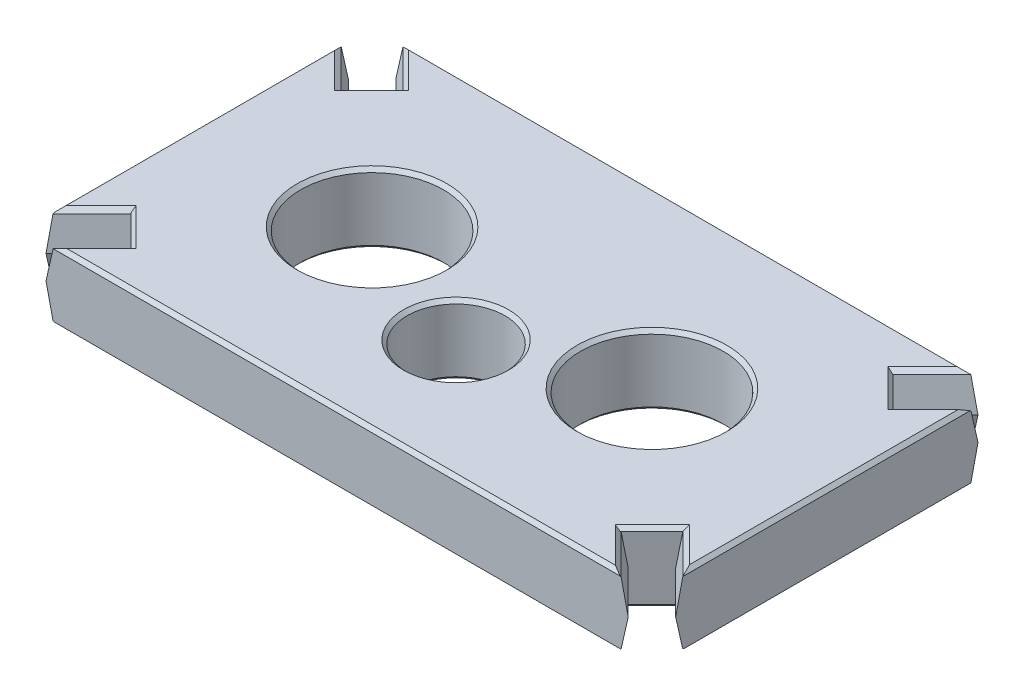
SolidWorks part; units mm, degrees
ref_plane "Front Plane" through (0, 0, 0) normal (0, 0, 1) x (1, 0, 0)
ref_plane "Top Plane" through (0, 0, 0) normal (0, 1, 0) x (1, 0, 0)
ref_plane "Right Plane" through (0, 0, 0) normal (1, 0, 0) x (0, 0, -1)
sketch "Sketch1" plane through (0, 0, 0) normal (0, 1, 0) x (1, 0, 0)
  line L0 (-10, 0) -> (10, 0) construction
  line L1 (-10, 12.5) -> (10, 12.5) construction
  line L2 (-10, -12.5) -> (10, -12.5) construction
  line L4 (22.5, -12.5) -> (-22.5, -12.5)
  line L5 (22.5, -12.5) -> (22.5, 12.5)
  line L6 (22.5, 12.5) -> (-22.5, 12.5)
  line L7 (-22.5, -12.5) -> (-22.5, 12.5)
  line L8 (22.5, -12.5) -> (-22.5, 12.5) construction
  line L9 (22.5, 12.5) -> (-22.5, -12.5) construction
  arc A0 (-10, 12.5) -> (-10, -12.5) centre (-10, 0) ccw construction
  arc A1 (10, -12.5) -> (10, 12.5) centre (10, 0) ccw construction
  circle A2 centre (-10, 0) radius 5.1
  circle A3 centre (10, 0) radius 5.1
  circle A4 centre (0, -4) radius 3.5
  point P2 (0, 0)
  point P12 (0, 0)
  point P19 (0, 0)
  dimension "D1" = 10.2
  dimension "D3" = 12.5
  dimension "D5" = 7
  dimension "D2" = 20
  dimension "D4" = 4
extrude "Boss-Extrude1" add sketch "Sketch1" along normal blind 5
ref_plane "Plane1" through (-17.5, 0, -17.5) normal (-0.7071, 0, -0.7071) x (0, -1, 0)
sketch "Sketch4" plane through (-17.5, 0, -17.5) normal (-0.7071, 0, -0.7071) x (0, -1, 0)
  line L0 (-5, 8.6711) -> (-5, 5.4711)
  line L1 (-5, 7.0711) -> (-5, 24.7487) construction
  line L2 (-5, -24.7487) -> (-5, 7.0711) construction
  line L3 (-5, 5.4711) -> (-2.5, 5.8711)
  line L4 (-2.5, 5.8711) -> (0, 5.4711)
  line L5 (0, -24.7487) -> (0, 7.0711) construction
  line L6 (0, 5.4711) -> (0, 8.6711)
  line L7 (0, 7.0711) -> (0, 24.7487) construction
  line L8 (0, 8.6711) -> (-2.5, 8.2711)
  line L9 (-2.5, 8.2711) -> (-5, 8.6711)
  line L10 (-2.5, 8.2711) -> (-2.5, 5.8711) construction
  line L11 (-5, 7.0711) -> (0, 7.0711) construction
  point P7 (-2.5, 7.0711)
  point P15 (0, 0)
  dimension "D1" = 3.2
  dimension "D2" = 2.4
extrude "Cut-Extrude3" cut sketch "Sketch4" against normal blind 5.5
mirror "Mirror1" about plane through (0, 0, 0) normal (0, 0, 1) of "Cut-Extrude3"
mirror "Mirror2" about plane through (0, 0, 0) normal (1, 0, 0) of "Mirror1", "Cut-Extrude3"
chamfer "Chamfer1" distance 0.25 angle 45 38 edges at (10, 0, 5.1) (-10, 0, 5.1) (21.1211, 0, -8.8584) (18.6109, 0, -8.6109) (18.8584, 0, -11.1211) (0, 0, -12.5) (-18.8584, 0, -11.1211) (-18.6109, 0, -8.6109) (-21.1211, 0, -8.8584) (-22.5, 0, 0) (-21.1211, 0, 8.8584) (-18.6109, 0, 8.6109) (-18.8584, 0, 11.1211) (0, 0, 12.5) (18.8584, 0, 11.1211) (18.6109, 0, 8.6109) (21.1211, 0, 8.8584) (22.5, 0, 0) (10, 5, 5.1) (-10, 5, 5.1) (18.6109, 5, 8.6109) (18.8584, 5, 11.1211) (0, 5, 12.5) (-18.8584, 5, 11.1211) (-18.6109, 5, 8.6109) (-21.1211, 5, 8.8584) (-22.5, 5, 0) (-21.1211, 5, -8.8584) (-18.6109, 5, -8.6109) (-18.8584, 5, -11.1211) (0, 5, -12.5) (18.8584, 5, -11.1211) (18.6109, 5, -8.6109) (21.1211, 5, -8.8584) (22.5, 5, 0) (21.1211, 5, 8.8584) (0, 0, 7.5) (0, 5, 7.5)
